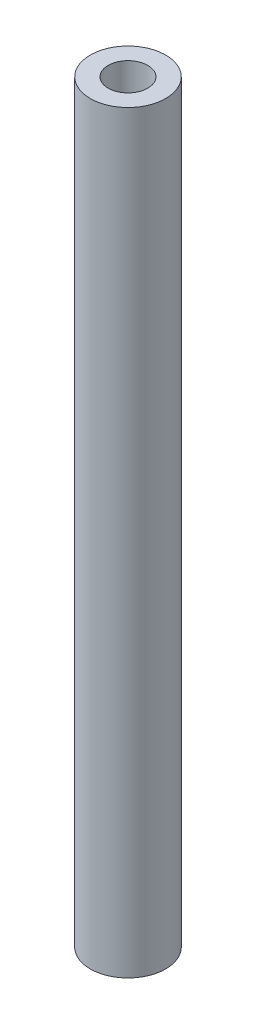
SolidWorks part; units mm, degrees
material "6063-T6"
ref_plane "Front Plane" through (0, 0, 0) normal (0, 0, 1) x (1, 0, 0)
ref_plane "Top Plane" through (0, 0, 0) normal (0, 1, 0) x (1, 0, 0)
ref_plane "Right Plane" through (0, 0, 0) normal (1, 0, 0) x (0, 0, -1)
sketch "Sketch1" plane through (0, 0, 0) normal (0, 1, 0) x (1, 0, 0)
  circle A0 centre (0, 0) radius 4
  dimension "D1" = 8
extrude "Boss-Extrude1" add sketch "Sketch1" along normal blind 80 and the other way blind 0.0001
hole_wizard "M5x0.8 Tapped Hole1" positions "Sketch2" profile "Sketch3" tap size "M5x0.8" standard "ANSI Metric"
sketch "Sketch2" plane through (0, 80, 0) normal (0, 1, 0) x (1, 0, 0)
  point P0 (0, 0)
sketch "Sketch3" plane through (0, 80, 0) normal (1, 0, 0) x (0, 0, 1)
  line L0 (0, 0) -> (0, 15.2618)
  line L1 (0, 15.2618) -> (2.1, 14)
  line L2 (2.1, 14) -> (2.1, 0)
  line L5 (2.1, 0) -> (0, 0)
  line L10 (0, 15.2618) -> (-2.1, 14) construction
  line L11 (0, -6.35) -> (0, 107.95) construction
  dimension "Tap Drill Dia." = 4.2
  dimension "Tap Drill Depth" = 14
  dimension "Drill Angle" = 118
cosmetic thread "Hole Thread1"
hole_wizard "M5x0.8 Tapped Hole2" positions "Sketch4" profile "Sketch5" tap size "M5x0.8" standard "ANSI Metric"
sketch "Sketch4" plane through (0, -0.0001, 0) normal (0, -1, 0) x (-1, 0, 0)
  point P0 (0, 0)
sketch "Sketch5" plane through (0, -0.0001, 0) normal (1, 0, 0) x (0, 0, -1)
  line L0 (0, 0) -> (0, 15.2618)
  line L1 (0, 15.2618) -> (2.1, 14)
  line L2 (2.1, 14) -> (2.1, 0)
  line L5 (2.1, 0) -> (0, 0)
  line L10 (0, 15.2618) -> (-2.1, 14) construction
  line L11 (0, -6.35) -> (0, 107.95) construction
  dimension "Tap Drill Dia." = 4.2
  dimension "Tap Drill Depth" = 14
  dimension "Drill Angle" = 118
cosmetic thread "Hole Thread2"
